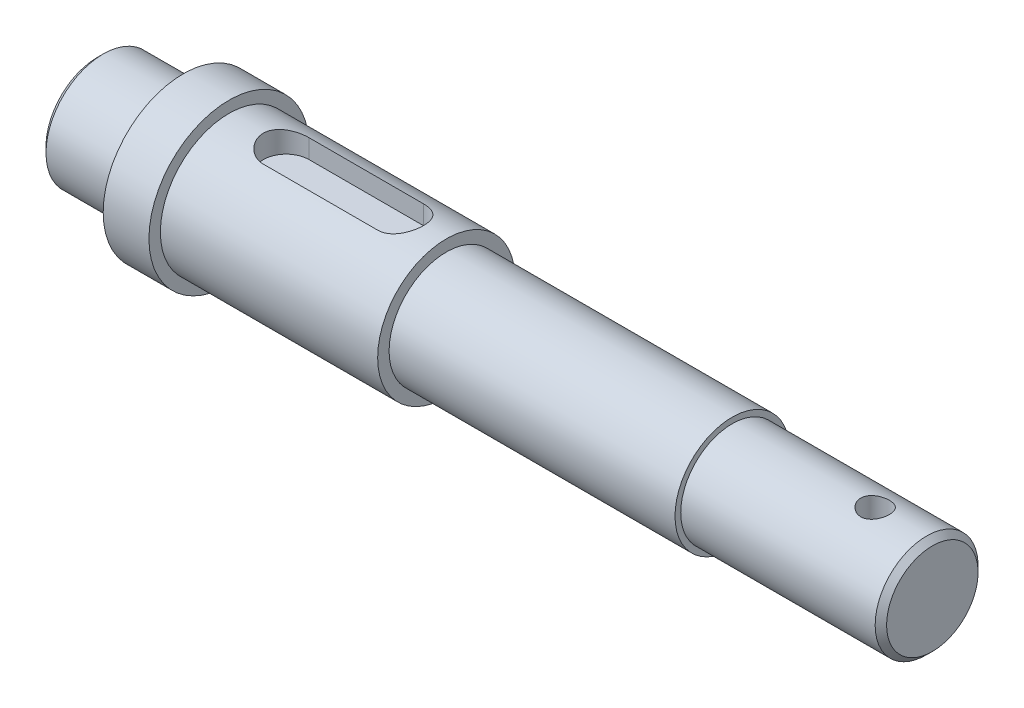
SolidWorks part; units mm, degrees
ref_plane "Front Plane" through (0, 0, 0) normal (0, 0, 1) x (1, 0, 0)
ref_plane "Top Plane" through (0, 0, 0) normal (0, 1, 0) x (1, 0, 0)
ref_plane "Right Plane" through (0, 0, 0) normal (1, 0, 0) x (0, 0, -1)
sketch "Sketch1" plane through (0, 0, 0) normal (0, 0, 1) x (1, 0, 0)
  line L0 (-99.4186, 0) -> (132.3837, 0) construction
  line L1 (-92.2674, 0) -> (-92.2674, 10)
  line L2 (-92.2674, 10) -> (-77.2674, 10)
  line L3 (-77.2674, 10) -> (-77.2674, 14)
  line L4 (-77.2674, 14) -> (-69.2674, 14)
  line L5 (-69.2674, 14) -> (-69.2674, 12)
  line L6 (-69.2674, 12) -> (-31.2674, 12)
  line L7 (-31.2674, 12) -> (-31.2674, 10)
  line L8 (-31.2674, 10) -> (18.7326, 10)
  line L9 (18.7326, 10) -> (18.7326, 9)
  line L10 (18.7326, 9) -> (53.7326, 9)
  line L11 (53.7326, 9) -> (53.7326, 0)
  line L12 (-92.2674, 0) -> (53.7326, 0)
  dimension "D1" = 15
  dimension "D2" = 146
  dimension "D3" = 8
  dimension "D4" = 85
  dimension "D5" = 35
  dimension "D6" = 20
  dimension "D7" = 28
  dimension "D8" = 24
  dimension "D9" = 20
  dimension "D10" = 18
revolve "Revolve1" add sketch "Sketch1" angle 360 about L0
chamfer "Chamfer1" distance 1 angle 45 2 edges at (53.7326, 0, 9) (-92.2674, 0, 10)
ref_plane "Plane1" through (0, 9, 0) normal (0, 1, 0) x (1, 0, 0)
sketch "Sketch2" plane through (0, 9, 0) normal (0, 1, 0) x (1, 0, 0)
  line L0 (53.7326, -8) -> (53.7326, 8) construction
  circle A0 centre (43.7326, 0) radius 2.5
  dimension "D1" = 10
extrude "Cut-Extrude1" cut sketch "Sketch2" against normal through all
ref_plane "Plane2" through (0, 12, 0) normal (0, 1, 0) x (1, 0, 0)
sketch "Sketch3" plane through (0, 12, 0) normal (0, 1, 0) x (1, 0, 0)
  line L0 (-59.2674, 0) -> (-39.2674, 0) construction
  line L1 (-59.2674, 4) -> (-39.2674, 4)
  line L2 (-59.2674, -4) -> (-39.2674, -4)
  line L3 (-69.2674, -12) -> (-69.2674, 12) construction
  arc A0 (-59.2674, 4) -> (-59.2674, -4) centre (-59.2674, 0) ccw
  arc A1 (-39.2674, -4) -> (-39.2674, 4) centre (-39.2674, 0) ccw
  point P3 (-49.2674, 0)
  dimension "D2" = 4
  dimension "D1" = 20
  dimension "D3" = 10
extrude "Cut-Extrude2" cut sketch "Sketch3" against normal blind 4
